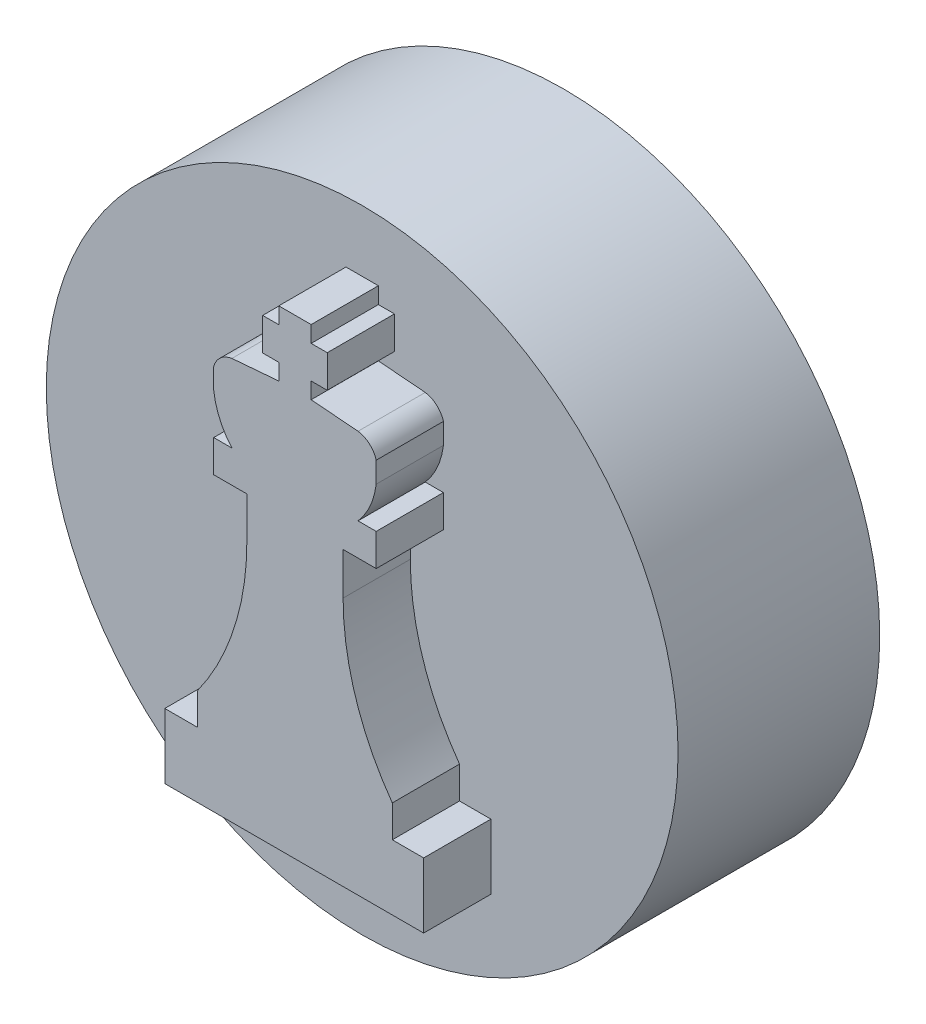
SolidWorks part; units mm, degrees
ref_plane "Front Plane" through (0, 0, 0) normal (0, 0, 1) x (1, 0, 0)
ref_plane "Top Plane" through (0, 0, 0) normal (0, 1, 0) x (1, 0, 0)
ref_plane "Right Plane" through (0, 0, 0) normal (1, 0, 0) x (0, 0, -1)
sketch "Sketch1" plane through (0, 0, 0) normal (0, 0, 1) x (1, 0, 0)
  circle A0 centre (0, 0) radius 8.763
  circle A1 centre (0, 0) radius 11.938
  dimension "D1" = 17.526
  dimension "D2" = 23.876
extrude "Boss-Extrude1" add sketch "Sketch1" along normal blind 5.08
sketch "Sketch2" plane through (0, 0, 5.08) normal (0, 0, 1) x (1, 0, 0)
  circle A0 centre (0, 0) radius 11.938
extrude "Boss-Extrude2" add sketch "Sketch2" along normal blind 2.54
sketch "Sketch3" plane through (0, 0, 7.62) normal (0, 0, 1) x (1, 0, 0)
  line L0 (76.4074, 247.7537) -> (417.7408, 247.7537) construction
  line L1 (0, 0) -> (0, 2.859) construction
  line L30 (33.3333, 100.0554) -> (166.6667, 100.0554) construction
  line L31 (76.5513, 248.4132) -> (417.8847, 248.4132) construction
  line L50 (33.4547, 119.6194) -> (204.1214, 119.6194) construction
  line L63 (146.8553, 495.6562) -> (829.522, 495.6562) construction
  line L64 (32.8546, 118.5983) -> (203.5213, 118.5983) construction
  line L65 (-3.6787, -5.7141) -> (-3.6787, -4.5057)
  line L66 (-0.6122, 9.6163) -> (0.6122, 9.6163)
  line L67 (-0.6122, 9.6163) -> (-0.6122, 8.9988)
  line L73 (-1.2201, 8.9988) -> (-1.2201, 7.7685)
  line L74 (-3.0703, 2.859) -> (-1.8192, 2.859)
  line L75 (-3.0703, 2.859) -> (-3.0703, 4.0767)
  line L76 (-3.0703, 4.0767) -> (-2.3837, 4.0767)
  line L78 (-4.92, -8.1735) -> (4.8631, -8.1735)
  line L79 (-4.92, -8.1735) -> (-4.92, -5.7141)
  line L80 (-4.92, -5.7141) -> (-3.6787, -5.7141)
  line L81 (4.8631, -8.1735) -> (4.8631, -5.7141)
  line L82 (-1.8192, 1.2671) -> (-1.8192, 2.859)
  line L83 (-2.3837, 7.0096) -> (-0.6122, 7.1558)
  line L84 (-3.0703, 6.4061) -> (-3.0703, 5.6215)
  line L85 (-0.6122, 8.9988) -> (-1.2201, 8.9988)
  line L86 (-0.6122, 7.7685) -> (-1.2201, 7.7685)
  line L87 (-0.6122, 7.7685) -> (-0.6122, 7.1558)
  line L88 (0, 4.0767) -> (0, 10.7108) construction
  line L89 (3.6787, -5.7141) -> (3.6787, -4.5057)
  line L90 (3.0703, 2.859) -> (1.8192, 2.859)
  line L91 (1.8192, 1.2671) -> (1.8192, 2.859)
  line L92 (3.0703, 2.859) -> (3.0703, 4.0767)
  line L93 (3.0703, 4.0767) -> (2.3837, 4.0767)
  line L94 (3.0703, 6.4061) -> (3.0703, 5.6215)
  line L95 (2.3837, 7.0096) -> (0.6122, 7.1558)
  line L96 (0.6122, 7.7685) -> (0.6122, 7.1558)
  line L97 (0.6122, 7.7685) -> (1.2201, 7.7685)
  line L98 (1.2201, 8.9988) -> (1.2201, 7.7685)
  line L99 (0.6122, 9.6163) -> (0.6122, 8.9988)
  line L100 (0.6122, 8.9988) -> (1.2201, 8.9988)
  line L101 (3.6787, -5.7141) -> (4.8631, -5.7141)
  arc A19 (-3.6787, -4.5057) -> (-1.8192, 1.2671) centre (-11.7098, 1.2671) ccw
  arc A20 (-2.3837, 4.0767) -> (-3.0703, 5.6215) centre (-0.2235, 5.9617) cw
  arc A21 (-2.3837, 7.0096) -> (-3.0703, 6.4061) centre (-2.2588, 6.1753) ccw
  arc A22 (3.6787, -4.5057) -> (1.8192, 1.2671) centre (11.7098, 1.2671) cw
  arc A23 (2.3837, 4.0767) -> (3.0703, 5.6215) centre (0.2235, 5.9617) ccw
  arc A24 (2.3837, 7.0096) -> (3.0703, 6.4061) centre (2.2588, 6.1753) cw
  point P59 (0, 9.6163)
extrude "Boss-Extrude6" add sketch "Sketch3" along normal blind 2.54 contours L82 L74 L75 L76 A20 L84 A21 L83 L87 L86 L73 L85 L67 L66 L99 L100 L98 L97 L96 L95 A24 L94 A23 L93 L92 L90 L91 A22 L89 L101 L81 L78 L79 L80 L65 A19
